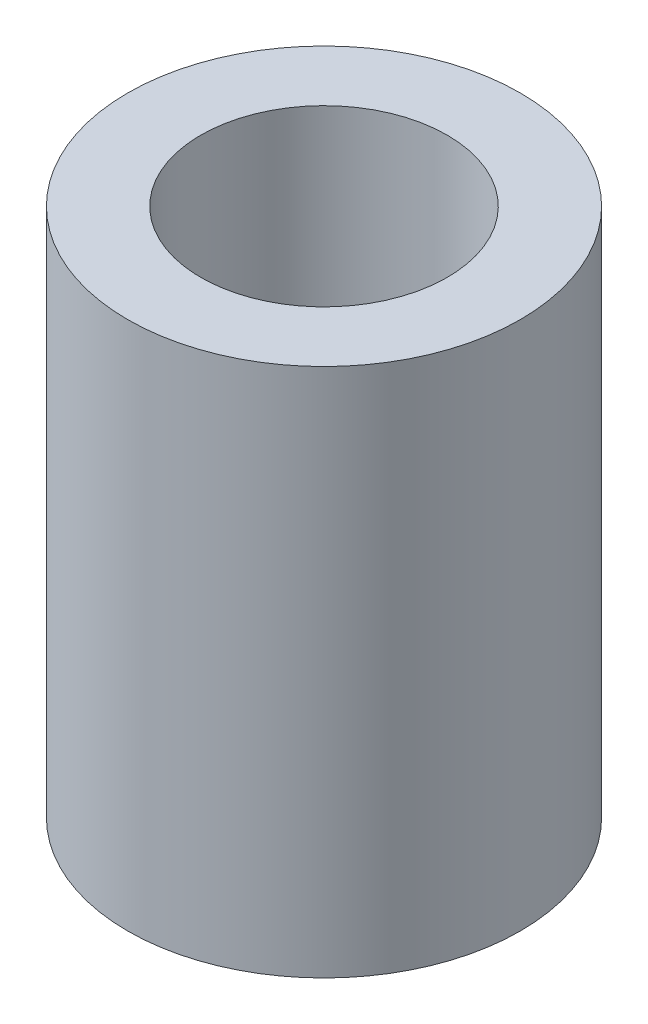
SolidWorks part; units mm, degrees
ref_plane "Front Plane" through (0, 0, 0) normal (0, 0, 1) x (1, 0, 0)
ref_plane "Top Plane" through (0, 0, 0) normal (0, 1, 0) x (1, 0, 0)
ref_plane "Right Plane" through (0, 0, 0) normal (1, 0, 0) x (0, 0, -1)
sketch "Sketch1" plane through (0, 0, 0) normal (0, 1, 0) x (1, 0, 0)
  circle A0 centre (0, 0) radius 3.375
  circle A1 centre (0, 0) radius 5.375
  dimension "D1" = 6.75
  dimension "D2" = 2
extrude "Boss-Extrude1" add sketch "Sketch1" along normal blind 14.5
